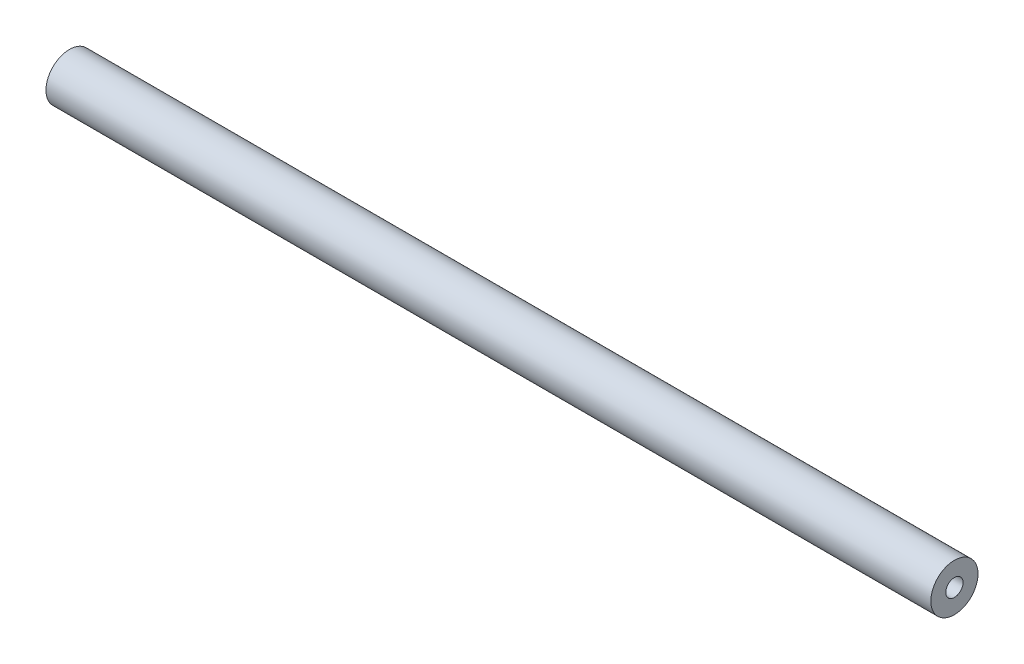
SolidWorks part; units mm, degrees
material "6061-T6 (SS)"
ref_plane "前视基准面" through (0, 0, 0) normal (0, 0, 1) x (1, 0, 0)
ref_plane "上视基准面" through (0, 0, 0) normal (0, 1, 0) x (1, 0, 0)
ref_plane "右视基准面" through (0, 0, 0) normal (1, 0, 0) x (0, 0, -1)
other "Configuration Table"
sketch "草图1" plane through (0, 0, 0) normal (1, 0, 0) x (0, 0, -1)
  circle A0 centre (0, 0) radius 1.65
  circle A1 centre (0, 0) radius 4.5
  dimension "D1" = 9
  dimension "D2" = 3.3
extrude "凸台-拉伸1" add sketch "草图1" along normal blind 168.9
